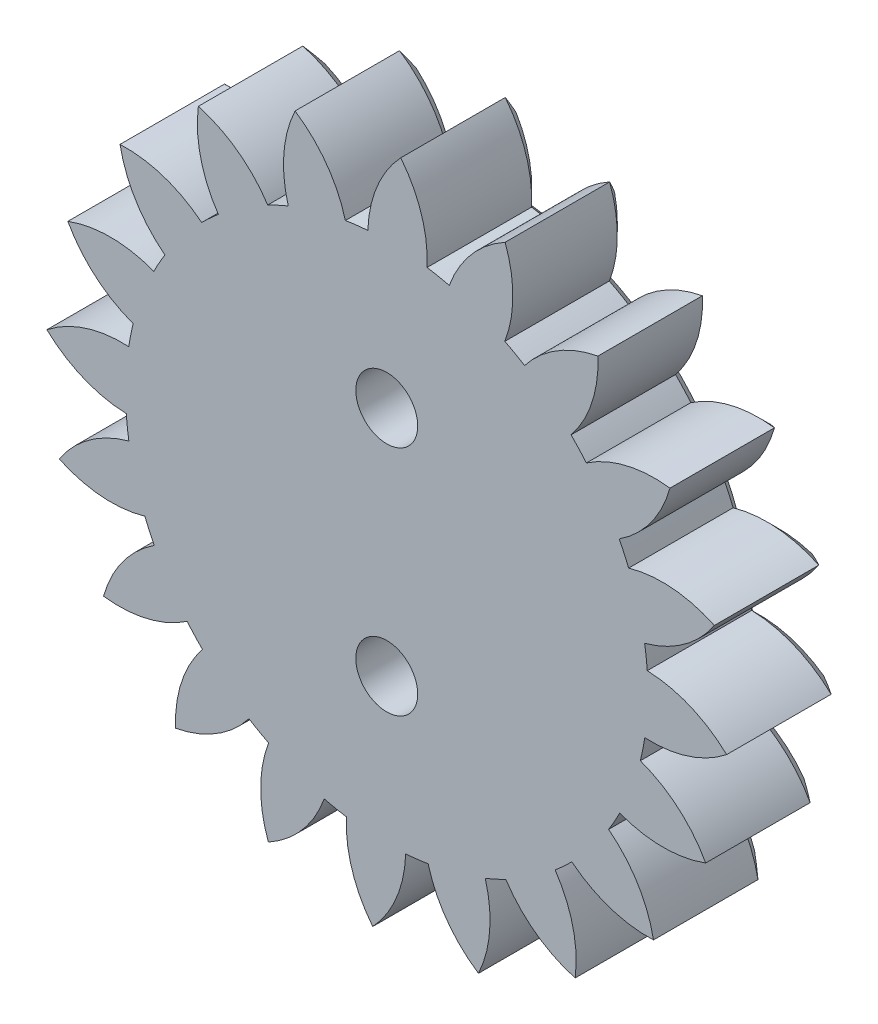
SolidWorks part; units mm, degrees
ref_plane "前视基准面" through (0, 0, 0) normal (0, 0, 1) x (1, 0, 0)
ref_plane "上视基准面" through (0, 0, 0) normal (0, 1, 0) x (1, 0, 0)
ref_plane "右视基准面" through (0, 0, 0) normal (1, 0, 0) x (0, 0, -1)
sketch "草图4" plane through (0, 0, 0) normal (0, 0, 1) x (1, 0, 0)
  arc A82 (6.7313, 0.4887) -> (6.6638, 1.0696) centre (0, 0) ccw
  arc A83 (6.6638, 1.0696) -> (8.4656, 2.3693) centre (5.8465, 4.1014) ccw
  arc A85 (8.5267, 2.3397) -> (6.2509, 2.5449) centre (7.1261, -0.4706) ccw
  arc A86 (6.2509, 2.5449) -> (6.0071, 3.0765) centre (0, 0) ccw
  arc A87 (6.0071, 3.0765) -> (7.3365, 4.935) centre (4.293, 5.7073) ccw
  arc A89 (7.3191, 4.8694) -> (5.1585, 4.352) centre (6.9228, 1.7545) ccw
  arc A90 (5.1585, 4.352) -> (4.7624, 4.7822) centre (0, 0) ccw
  arc A91 (4.7624, 4.7822) -> (5.4562, 6.8928) centre (2.3192, 6.7546) ccw
  arc A93 (5.523, 6.9047) -> (3.5612, 5.733) centre (6.0418, 3.8079) ccw
  arc A94 (3.5612, 5.733) -> (3.0515, 6.0198) centre (0, 0) ccw
  arc A95 (3.0515, 6.0198) -> (3.0591, 8.2415) centre (0.1184, 7.1407) ccw
  arc A97 (3.119, 8.2735) -> (1.6153, 6.5529) centre (4.5694, 5.4885) ccw
  arc A98 (1.6153, 6.5529) -> (1.042, 6.6681) centre (0, 0) ccw
  arc A99 (1.042, 6.6681) -> (0.3626, 8.7834) centre (-2.094, 6.8278) ccw
  arc A101 (0.4097, 8.8324) -> (-0.4887, 6.7313) centre (2.6497, 6.6319) ccw
  arc A102 (-0.4887, 6.7313) -> (-1.0696, 6.6638) centre (0, 0) ccw
  arc A103 (-1.0696, 6.6638) -> (-2.3693, 8.4656) centre (-4.1014, 5.8465) ccw
  arc A105 (-2.3397, 8.5267) -> (-2.5449, 6.2509) centre (0.4706, 7.1261) ccw
  arc A106 (-2.5449, 6.2509) -> (-3.0765, 6.0071) centre (0, 0) ccw
  arc A107 (-3.0765, 6.0071) -> (-4.8694, 7.3191) centre (-5.7073, 4.293) ccw
  arc A109 (-4.8601, 7.3863) -> (-4.352, 5.1585) centre (-1.7545, 6.9228) ccw
  arc A110 (-4.352, 5.1585) -> (-4.7822, 4.7624) centre (0, 0) ccw
  arc A111 (-4.7822, 4.7624) -> (-6.8928, 5.4562) centre (-6.7546, 2.3192) ccw
  arc A113 (-6.9047, 5.523) -> (-5.733, 3.5612) centre (-3.8079, 6.0418) ccw
  arc A114 (-5.733, 3.5612) -> (-6.0198, 3.0515) centre (0, 0) ccw
  arc A115 (-6.0198, 3.0515) -> (-8.3048, 3.0347) centre (-7.1407, 0.1184) ccw
  arc A117 (-8.2415, 3.0591) -> (-6.5529, 1.6153) centre (-5.4885, 4.5694) ccw
  arc A118 (-6.5529, 1.6153) -> (-6.6681, 1.042) centre (0, 0) ccw
  arc A119 (-6.6681, 1.042) -> (-8.7834, 0.3626) centre (-6.8278, -2.094) ccw
  arc A121 (-8.8324, 0.4097) -> (-6.7313, -0.4887) centre (-6.6319, 2.6497) ccw
  arc A122 (-6.7313, -0.4887) -> (-6.6638, -1.0696) centre (0, 0) ccw
  arc A123 (-6.6638, -1.0696) -> (-8.4656, -2.3693) centre (-5.8465, -4.1014) ccw
  arc A125 (-8.5267, -2.3397) -> (-6.2509, -2.5449) centre (-7.1261, 0.4706) ccw
  arc A126 (-6.2509, -2.5449) -> (-6.0071, -3.0765) centre (0, 0) ccw
  arc A127 (-6.0071, -3.0765) -> (-7.3191, -4.8694) centre (-4.293, -5.7073) ccw
  arc A129 (-7.3863, -4.8601) -> (-5.1585, -4.352) centre (-6.9228, -1.7545) ccw
  arc A130 (-5.1585, -4.352) -> (-4.7624, -4.7822) centre (0, 0) ccw
  arc A131 (-4.7624, -4.7822) -> (-5.4562, -6.8928) centre (-2.3192, -6.7546) ccw
  arc A133 (-5.523, -6.9047) -> (-3.5612, -5.733) centre (-6.0418, -3.8079) ccw
  arc A134 (-3.5612, -5.733) -> (-3.0515, -6.0198) centre (0, 0) ccw
  arc A135 (-3.0515, -6.0198) -> (-3.0347, -8.3048) centre (-0.1184, -7.1407) ccw
  arc A137 (-3.0591, -8.2415) -> (-1.6153, -6.5529) centre (-4.5694, -5.4885) ccw
  arc A138 (-1.6153, -6.5529) -> (-1.042, -6.6681) centre (0, 0) ccw
  arc A139 (-1.042, -6.6681) -> (-0.3626, -8.7834) centre (2.094, -6.8278) ccw
  arc A141 (-0.4097, -8.8324) -> (0.4887, -6.7313) centre (-2.6497, -6.6319) ccw
  arc A142 (0.4887, -6.7313) -> (1.0696, -6.6638) centre (0, 0) ccw
  arc A143 (1.0696, -6.6638) -> (2.3693, -8.4656) centre (4.1014, -5.8465) ccw
  arc A145 (2.3397, -8.5267) -> (2.5449, -6.2509) centre (-0.4706, -7.1261) ccw
  arc A146 (2.5449, -6.2509) -> (3.0765, -6.0071) centre (0, 0) ccw
  arc A147 (3.0765, -6.0071) -> (4.8694, -7.3191) centre (5.7073, -4.293) ccw
  arc A149 (4.8601, -7.3863) -> (4.352, -5.1585) centre (1.7545, -6.9228) ccw
  arc A150 (4.352, -5.1585) -> (4.7822, -4.7624) centre (0, 0) ccw
  arc A151 (4.7822, -4.7624) -> (6.8928, -5.4562) centre (6.7546, -2.3192) ccw
  arc A153 (6.9047, -5.523) -> (5.733, -3.5612) centre (3.8079, -6.0418) ccw
  arc A154 (5.733, -3.5612) -> (6.0198, -3.0515) centre (0, 0) ccw
  arc A155 (6.0198, -3.0515) -> (8.2415, -3.0591) centre (7.1407, -0.1184) ccw
  arc A157 (8.2735, -3.119) -> (6.5529, -1.6153) centre (5.4885, -4.5694) ccw
  arc A158 (6.5529, -1.6153) -> (6.6681, -1.042) centre (0, 0) ccw
  arc A159 (6.6681, -1.042) -> (8.7834, -0.3626) centre (6.8278, 2.094) ccw
  arc A161 (8.8324, -0.4097) -> (6.7313, 0.4887) centre (6.6319, -2.6497) ccw
  circle A162 centre (0, 0) radius 8.8419
extrude "凸台-拉伸4" add sketch "草图4" along normal blind 3
sketch "草图5" plane through (0, 0, 0) normal (0, 0, -1) x (-1, 0, 0)
  line L0 (0, 0) -> (3.9024, 0) construction
  line L1 (0, 0) -> (0, 9.6034) construction
  circle A0 centre (0, 3) radius 0.8
  circle A1 centre (0, -3) radius 0.8
  dimension "D1" = 3
  dimension "D2" = 1.6
extrude "切除-拉伸1" cut sketch "草图5" against normal up to next
chamfer "倒角1" distance 0.3 angle 45 62 edges at (7.8352, 0.2506, 0) (6.7038, 0.7799, 0) (7.6835, 1.5548, 0) (7.3743, 2.6595, 0) (6.1347, 2.8133, 0) (6.827, 3.853, 0) (6.1915, 4.8082, 0) (4.9651, 4.5714, 0) (5.3022, 5.7741, 0) (4.4027, 6.4861, 0) (3.3095, 5.8819, 0) (3.2584, 7.1299, 0) (2.1829, 7.5292, 0) (1.3299, 6.6167, 0) (0.8956, 7.7879, 0) (-0.2506, 7.8352, 0) (-0.7799, 6.7038, 0) (-1.5548, 7.6835, 0) (-2.6595, 7.3743, 0) (-2.8133, 6.1347, 0) (-3.853, 6.827, 0) (-4.8082, 6.1915, 0) (-4.5714, 4.9651, 0) (-5.7741, 5.3022, 0) (-6.4861, 4.4027, 0) (-5.8819, 3.3095, 0) (-7.1299, 3.2584, 0) (-7.5292, 2.1829, 0) (-6.6167, 1.3299, 0) (-7.7879, 0.8956, 0) (-7.8352, -0.2506, 0) (-6.7038, -0.7799, 0) (-7.6835, -1.5548, 0) (-7.3743, -2.6595, 0) (-6.1347, -2.8133, 0) (-6.827, -3.853, 0) (-6.1915, -4.8082, 0) (-4.9651, -4.5714, 0) (-5.3022, -5.7741, 0) (-4.4027, -6.4861, 0) (-3.3095, -5.8819, 0) (-3.2584, -7.1299, 0) (-2.1829, -7.5292, 0) (-1.3299, -6.6167, 0) (-0.8956, -7.7879, 0) (0.2506, -7.8352, 0) (0.7799, -6.7038, 0) (1.5548, -7.6835, 0) (2.6595, -7.3743, 0) (2.8133, -6.1347, 0) (3.853, -6.827, 0) (4.8082, -6.1915, 0) (4.5714, -4.9651, 0) (5.7741, -5.3022, 0) (6.4861, -4.4027, 0) (5.8819, -3.3095, 0) (7.1299, -3.2584, 0) (7.5292, -2.1829, 0) (6.6167, -1.3299, 0) (7.7879, -0.8956, 0) (0.8, -3, 0) (-0.8, 3, 0)
